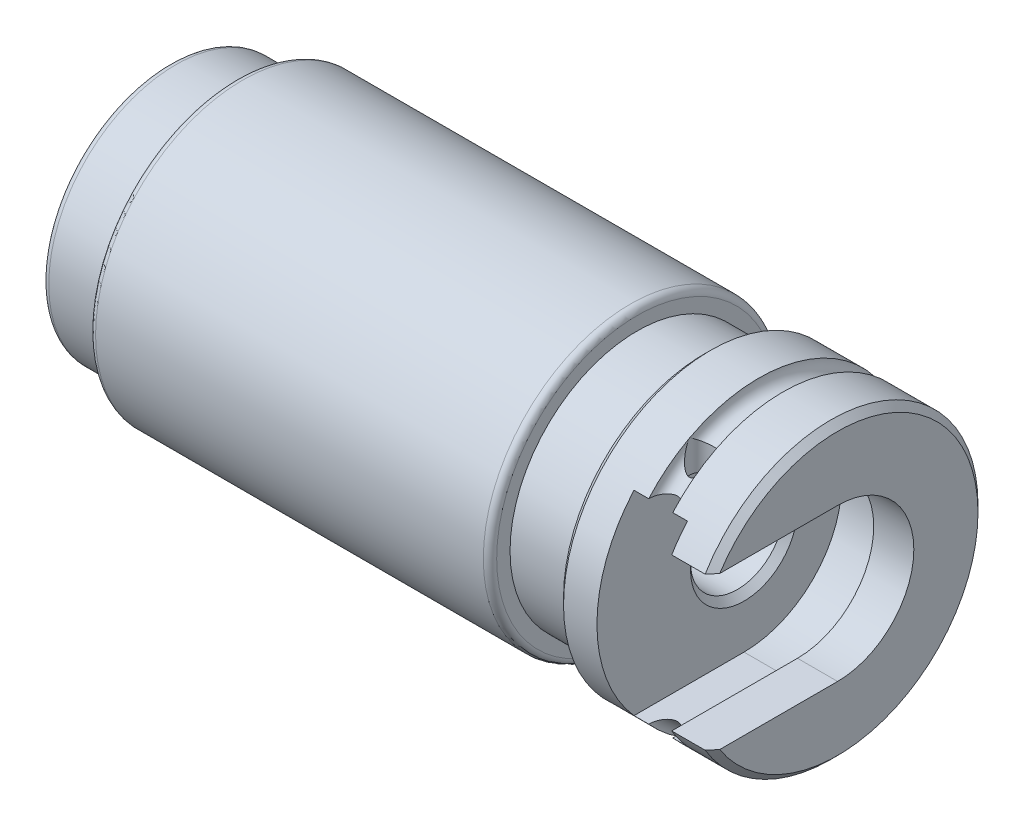
SolidWorks part; units mm, degrees
material "AISI 1020"
ref_plane "Plano superior" through (0, 0, 0) normal (0, 0, 1) x (1, 0, 0)
ref_plane "Plano frontal" through (0, 0, 0) normal (0, 1, 0) x (1, 0, 0)
ref_plane "Plano direito" through (0, 0, 0) normal (1, 0, 0) x (0, 0, -1)
sketch "Esboço1" plane through (0, 0, 0) normal (0, 1, 0) x (1, 0, 0)
  line L0 (0, 0) -> (0, 3.5) construction
  line L1 (0, 3.5) -> (43, 3.5)
  line L2 (43, 3.5) -> (43, 7.3)
  line L3 (43, 7.3) -> (47, 7.3)
  line L4 (47, 7.3) -> (47, 5.7)
  line L5 (47, 5.7) -> (50, 5.7)
  line L6 (50, 11) -> (45.9, 11)
  line L7 (40, 11) -> (40, 9.5)
  line L8 (40, 9.5) -> (35, 9.5)
  line L9 (35, 9.5) -> (35, 11)
  line L10 (35, 11) -> (5, 11)
  line L11 (5, 11) -> (5, 9.5)
  line L12 (5, 9.5) -> (0, 9.5)
  line L13 (0, 9.5) -> (0, 3.5)
  line L14 (50, 11) -> (50, 5.7)
  line L15 (0, 0) -> (65.7514, 0) construction
  line L16 (45, 7.3) -> (45, 11) construction
  line L17 (44.1, 11) -> (40, 11)
  arc A0 (44.1, 11) -> (45.9, 11) centre (45, 11) ccw
  point P22 (40, 10.25)
  point P23 (5, 10.25)
  dimension "D1" = 43
  dimension "D10" = 1.8
  dimension "D2" = 4
  dimension "D3" = 3
  dimension "D4" = 3.5
  dimension "D5" = 11
  dimension "D6" = 9.5
  dimension "D7" = 7.3
  dimension "D8" = 9.5
  dimension "D9" = 11
  dimension "D11" = 5.7
  dimension "D12" = 50
  dimension "D13" = 10
  dimension "D14" = 3.7
  dimension "D15" = 5
  dimension "D16" = 30
revolve "Revolução1" add sketch "Esboço1" angle 360 about L15
cosmetic thread "Representação de rosca1" parameters "D2"=6.619
cosmetic thread "Representação de rosca2" parameters "D2"=6.619
cosmetic thread "Representação de rosca3" parameters "D2"=19.252
sketch "Esboço2" plane through (50, 0, 0) normal (1, 0, 0) x (0, 0, -1)
  line L0 (0, 5.7) -> (0, -5.7) construction
  line L2 (0, 5.7) -> (-11.0922, 5.7)
  line L3 (0, 5.7) -> (0, -5.7)
  line L4 (0, -5.7) -> (-11.0922, -5.7)
  line L5 (-11.0922, 5.7) -> (-11.0922, -5.7)
  circle A0 centre (0, 0) radius 5.7 construction
extrude "Corte-extrusão1" cut sketch "Esboço2" against normal blind 3
sketch "Esboço6" plane through (43, 0, 0) normal (1, 0, 0) x (0, 0, -1)
  line L0 (0, 0) -> (0, 7.3) construction
  line L1 (0, 0) -> (0, -7.3) construction
  line L3 (0, 7.3) -> (-12.1023, 7.3)
  line L4 (0, 7.3) -> (0, -7.3)
  line L5 (0, -7.3) -> (-12.1023, -7.3)
  line L6 (-12.1023, 7.3) -> (-12.1023, -7.3)
  circle A0 centre (0, 0) radius 7.3 construction
extrude "Corte-extrusão2" cut sketch "Esboço6" along normal blind 4
chamfer "Chanfro1" distance 1 angle 45 1 edges at (0, 0, 3.5)
fillet "Filete1" radius 0.5 1 edges at (0, 0, 9.5)
chamfer "Chanfro2" distance 0.5 angle 45 2 edges at (50, 0, -11) (40, 0, 11)
chamfer "Chanfro3" distance 0.5 angle 45 1 edges at (43, 0, 3.5)
sketch "Esboço7" plane through (0, 7.3, 0) normal (0, -1, 0) x (1, 0, 0)
  circle A0 centre (44.9971, 5.18) radius 0.9
  dimension "D2" = 1.8
extrude "Corte-extrusão3" cut sketch "Esboço7" against normal up to next
fillet "Filete2" radius 0.5 1 edges at (5, 0, 11)
fillet "Filete3" radius 0.5 1 edges at (35, 0, 11)
